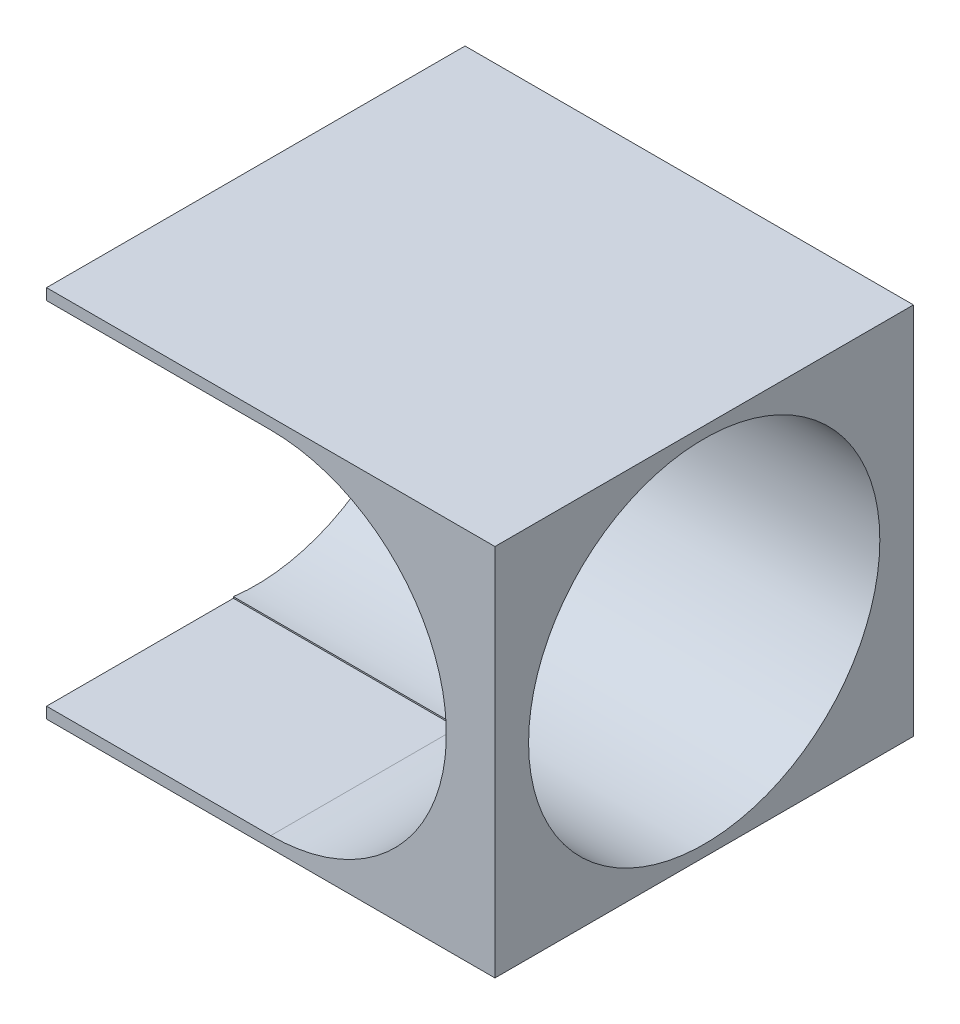
SolidWorks part; units mm, degrees
ref_plane "Front Plane" through (0, 0, 0) normal (0, 0, 1) x (1, 0, 0)
ref_plane "Top Plane" through (0, 0, 0) normal (0, 1, 0) x (1, 0, 0)
ref_plane "Right Plane" through (0, 0, 0) normal (1, 0, 0) x (0, 0, -1)
sketch "Sketch1" plane through (0, 0, 0) normal (0, 1, 0) x (1, 0, 0)
  line L1 (-15, 14) -> (15, 14)
  line L2 (-15, 14) -> (-15, -14)
  line L3 (-15, -14) -> (15, -14)
  line L4 (15, 14) -> (15, -14)
  line L5 (-15, 14) -> (15, -14) construction
  line L6 (-15, -14) -> (15, 14) construction
  point P0 (0, 0)
  dimension "D1" = 28
  dimension "D2" = 30
extrude "Boss-Extrude1" add sketch "Sketch1" along normal blind 25
sketch "Sketch2" plane through (-15, 0, 0) normal (-1, 0, 0) x (0, 0, 1)
  line L0 (0, -55) -> (0, 55) construction
  line L1 (55, 0) -> (-55, 0) construction
  circle A0 centre (0, 12.5) radius 11.75
  dimension "D1" = 23.5
  dimension "D2" = 12.5
extrude "Cut-Extrude1" cut sketch "Sketch2" against normal through all
sketch "Sketch3" plane through (0, 0, 14) normal (0, 0, 1) x (1, 0, 0)
  line L0 (0, -55) -> (0, 55) construction
  line L1 (55, 0) -> (-55, 0) construction
  line L2 (0, 24.25) -> (-15, 24.25)
  line L3 (0, 0.75) -> (-15, 0.75)
  line L4 (-15, 0.75) -> (-15, 24.25)
  line L5 (-15, 25) -> (15, 25) construction
  line L6 (-15, 25) -> (-15, 0) construction
  arc A0 (0, 0.75) -> (0, 24.25) centre (0, 12.5) ccw
  point P1 (0, 0)
  point P16 (0, 0)
  dimension "D1" = 23.5
  dimension "D2" = 12.5
  dimension "D3" = 0.75
extrude "Cut-Extrude2" cut sketch "Sketch3" against normal blind 12.5
